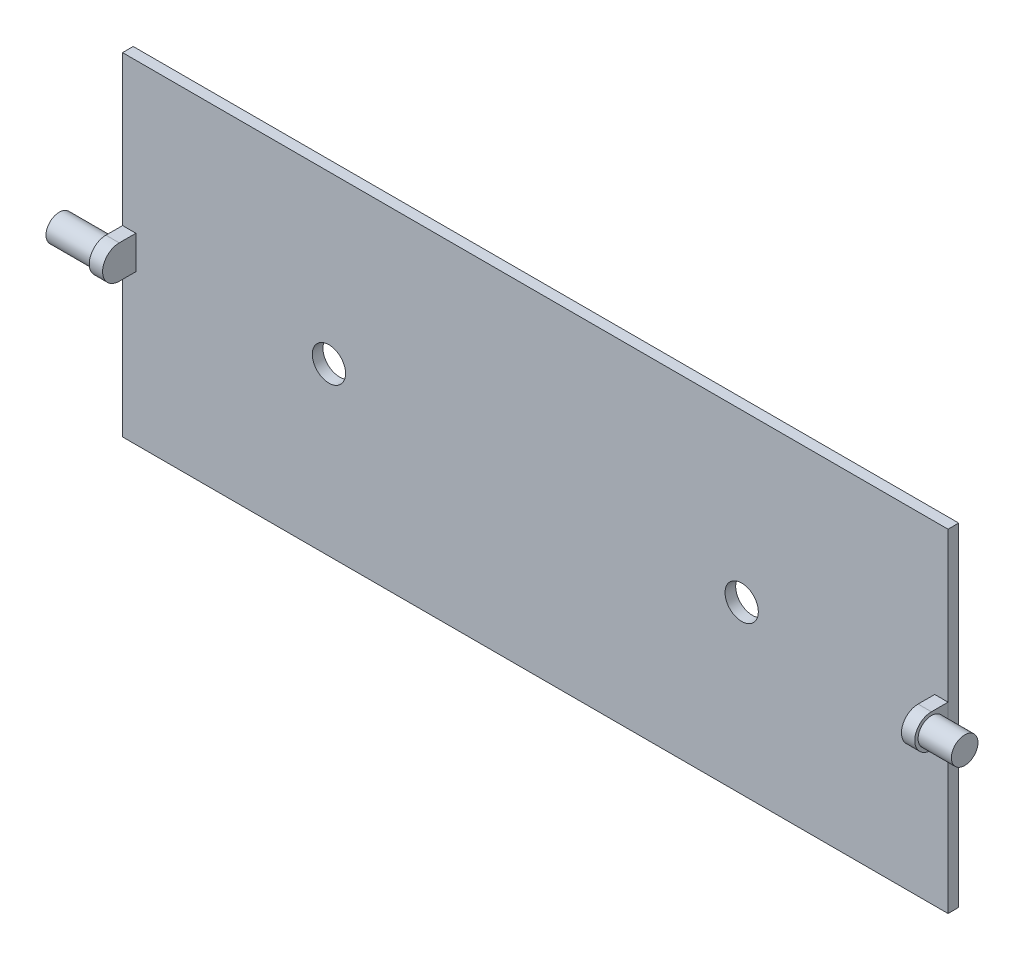
SolidWorks part; units mm, degrees
ref_plane "Front Plane" through (0, 0, 0) normal (0, 0, 1) x (1, 0, 0)
ref_plane "Top Plane" through (0, 0, 0) normal (0, 1, 0) x (1, 0, 0)
ref_plane "Right Plane" through (0, 0, 0) normal (1, 0, 0) x (0, 0, -1)
sketch "Sketch1" plane through (0, 0, 0) normal (0, 0, 1) x (1, 0, 0)
  line L1 (-310, -125) -> (310, -125)
  line L2 (-310, -125) -> (-310, 125)
  line L3 (-310, 125) -> (310, 125)
  line L4 (310, -125) -> (310, 125)
  line L5 (-310, -125) -> (310, 125) construction
  line L6 (-310, 125) -> (310, -125) construction
  point P0 (0, 0)
  dimension "D1" = 250
  dimension "D2" = 620
extrude "Boss-Extrude1" add sketch "Sketch1" along normal blind 8
sketch "Sketch2" plane through (0, 0, 8) normal (0, 0, 1) x (1, 0, 0)
  line L0 (0, 0) -> (0, 159.9174) construction
  line L1 (-437.6658, 0) -> (441.4397, 0) construction
  circle A0 centre (155, 0) radius 12.5
  circle A1 centre (-155, 0) radius 12.5
  dimension "D1" = 25
  dimension "D2" = 155
extrude "Cut-Extrude1" cut sketch "Sketch2" against normal blind 8
sketch "Sketch3" plane through (310, 0, 0) normal (1, 0, 0) x (0, 0, -1)
  line L0 (-8, -125) -> (-8, 125) construction
  line L1 (-20.5, 12.5) -> (-8, 12.5)
  line L3 (-8, 12.5) -> (-8, -12.5)
  line L4 (-8, -12.5) -> (-20.5, -12.5)
  line L5 (-8, -12.5) -> (-8.2949, -12.5905)
  arc A0 (-20.5, 12.5) -> (-20.5, -12.5) centre (-20.5, 0) ccw
  dimension "D1" = 25
extrude "Boss-Extrude2" add sketch "Sketch3" against normal blind 10 separate body contours L4 A0 L1 L3
sketch "Sketch4" plane through (310, 0, 0) normal (1, 0, 0) x (0, 0, -1)
  circle A0 centre (-20.5, 0) radius 10
  dimension "D1" = 20
extrude "Boss-Extrude3" add sketch "Sketch4" along normal blind 25 separate body
mirror "Mirror2" about plane through (0, 0, 0) normal (1, 0, 0) of "Boss-Extrude2", "Boss-Extrude3"
sketch "Sketch5" plane through (-310, 0, 0) normal (-1, 0, 0) x (0, 0, 1)
  circle A0 centre (20.5, 0) radius 10
  dimension "D1" = 20
extrude "Boss-Extrude4" add sketch "Sketch5" along normal blind 35 separate body
